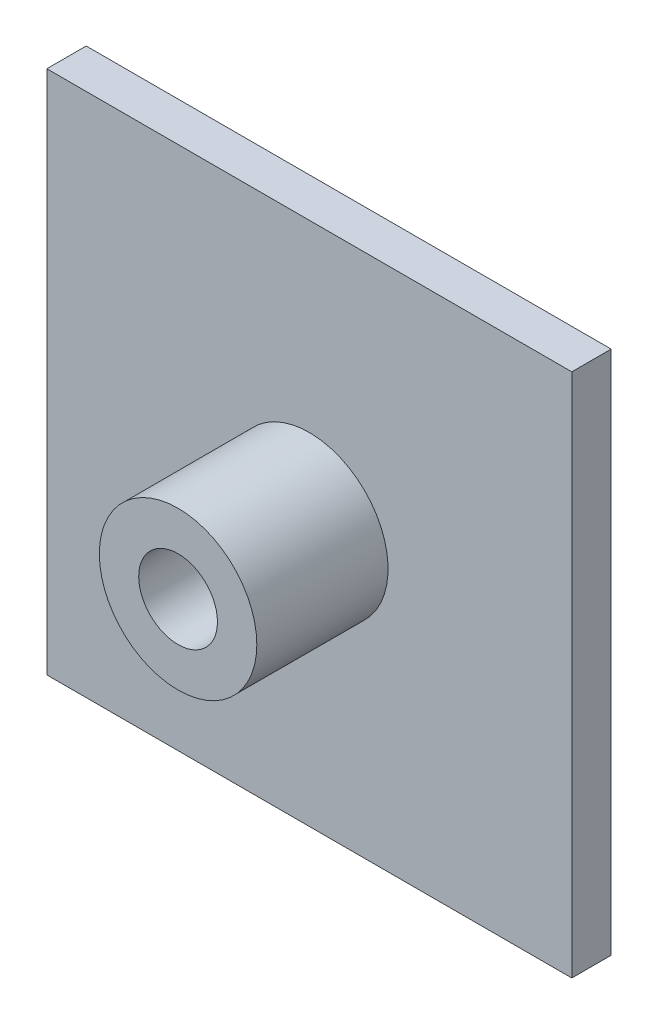
SolidWorks part; units mm, degrees
material "Сосна"
ref_plane "Front" through (0, 0, 0) normal (0, 0, 1) x (1, 0, 0)
ref_plane "Top" through (0, 0, 0) normal (0, 1, 0) x (1, 0, 0)
ref_plane "Right" through (0, 0, 0) normal (1, 0, 0) x (0, 0, -1)
sketch "Эскиз2" plane through (0, 0, 0) normal (0, 0, 1) x (1, 0, 0)
  line L1 (-10, -10) -> (10, -10)
  line L2 (-10, -10) -> (-10, 10)
  line L3 (-10, 10) -> (10, 10)
  line L4 (10, -10) -> (10, 10)
  line L5 (-10, -10) -> (10, 10) construction
  line L6 (-10, 10) -> (10, -10) construction
  circle A0 centre (0, 0) radius 1.5
  point P0 (0, 0)
  dimension "D2" = 3
  dimension "D1" = 20
extrude "Основание" add sketch "Эскиз2" along normal blind 1.5
sketch "Эскиз3" plane through (0, 0, 1.5) normal (0, 0, 1) x (1, 0, 0)
  circle A0 centre (0, 0) radius 3
  circle A3 centre (0, 0) radius 1.5
  circle A4 centre (0, 0) radius 1.5 construction
  dimension "D1" = 6
  dimension "D2" = 1.5
extrude "Стойка" add sketch "Эскиз3" along normal blind 5
chamfer "Фаска1" distance 1.5 angle 45 1 edges at (1.5, 0, 0)
